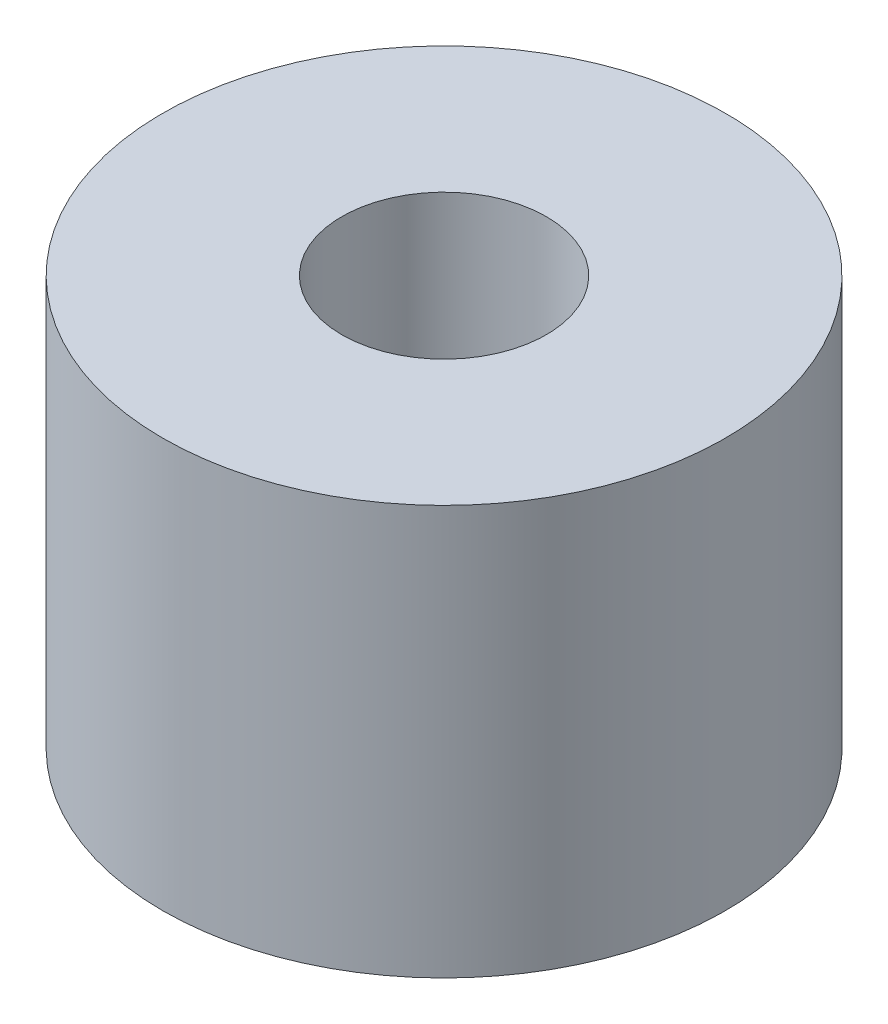
SolidWorks part; units mm, degrees
ref_plane "Front Plane" through (0, 0, 0) normal (0, 0, 1) x (1, 0, 0)
ref_plane "Top Plane" through (0, 0, 0) normal (0, 1, 0) x (1, 0, 0)
ref_plane "Right Plane" through (0, 0, 0) normal (1, 0, 0) x (0, 0, -1)
sketch "Sketch1" plane through (0, 0, 0) normal (0, 1, 0) x (1, 0, 0)
  circle A0 centre (0, 0) radius 4
  circle A1 centre (0, 0) radius 11
  dimension "D1" = 8
  dimension "D2" = 22
extrude "Boss-Extrude1" add sketch "Sketch1" along normal blind 16
